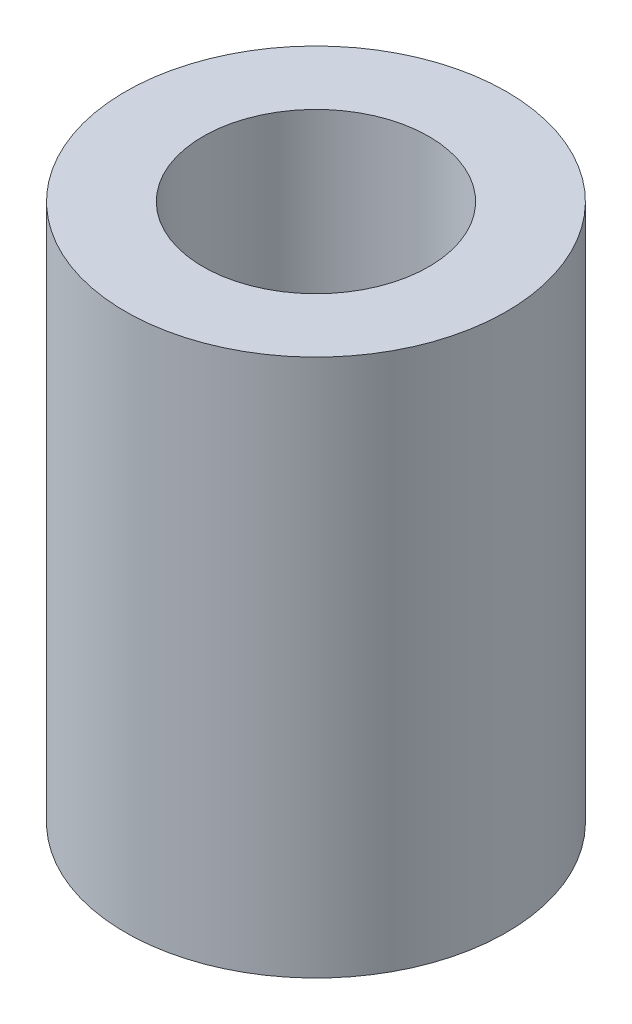
SolidWorks part; units mm, degrees
ref_plane "Front Plane" through (0, 0, 0) normal (0, 0, 1) x (1, 0, 0)
ref_plane "Top Plane" through (0, 0, 0) normal (0, 1, 0) x (1, 0, 0)
ref_plane "Right Plane" through (0, 0, 0) normal (1, 0, 0) x (0, 0, -1)
sketch "Sketch1" plane through (0, 0, 0) normal (0, 1, 0) x (1, 0, 0)
  circle A0 centre (0, 0) radius 2.7
  circle A1 centre (0, 0) radius 1.6
  dimension "D1" = 3.2
  dimension "D2" = 5.4
extrude "Boss-Extrude1" add sketch "Sketch1" along normal blind 7.62
